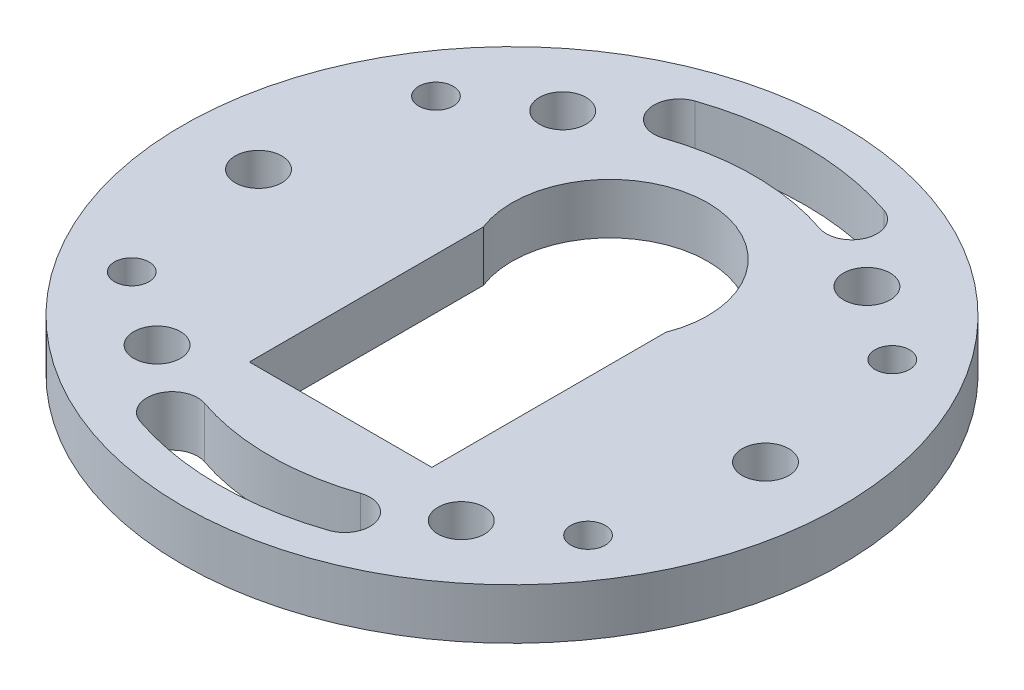
SolidWorks part; units mm, degrees
ref_plane "Front Plane" through (0, 0, 0) normal (0, 0, 1) x (1, 0, 0)
ref_plane "Top Plane" through (0, 0, 0) normal (0, 1, 0) x (1, 0, 0)
ref_plane "Right Plane" through (0, 0, 0) normal (1, 0, 0) x (0, 0, -1)
sketch "Sketch1" plane through (0, 0, 0) normal (0, 1, 0) x (1, 0, 0)
  line L0 (-15, -20) -> (-15, 20) construction
  line L1 (0, 0) -> (-25, 0) construction
  line L2 (-22.5, 15) -> (-22.5, -15) construction
  line L3 (0, 0) -> (0, 22.3159) construction
  line L4 (-8.5, 25) -> (8.5, 25) construction
  line L5 (0, 0) -> (15.5017, 0) construction
  line L6 (-8.5, -25) -> (8.5, -25) construction
  line L7 (0, -16.9) -> (0, 19.3) construction
  line L9 (-9, 6.1683) -> (-9, -16.9)
  line L10 (-9, -16.9) -> (9, -16.9)
  line L11 (9, 6.1683) -> (9, -16.9)
  line L12 (-6.4793, 8.3755) -> (9, -16.9) construction
  line L13 (-9, -16.9) -> (6.95, 9.1441) construction
  circle A0 centre (-15, 20) radius 2.3
  circle A1 centre (-22.5, 15) radius 1.7
  circle A2 centre (-15, -20) radius 2.3
  circle A3 centre (-25, 0) radius 2.3
  circle A4 centre (-22.5, -15) radius 1.7
  circle A5 centre (15, -20) radius 2.3
  circle A6 centre (22.5, -15) radius 1.7
  circle A7 centre (25, 0) radius 2.3
  circle A8 centre (22.5, 15) radius 1.7
  circle A9 centre (15, 20) radius 2.3
  circle A11 centre (0, 0) radius 32.5
  arc A12 (7.6952, 22.6331) -> (9.3048, 27.3669) centre (8.5, 25) ccw
  arc A13 (-9.3048, 27.3669) -> (-7.6952, 22.6331) centre (-8.5, 25) ccw
  arc A14 (-9.3048, 27.3669) -> (9.3048, 27.3669) centre (0, 0) cw
  arc A15 (-7.6952, 22.6331) -> (7.6952, 22.6331) centre (0, 0) cw
  arc A16 (7.6952, -22.6331) -> (9.3048, -27.3669) centre (8.5, -25) cw
  arc A17 (-9.3048, -27.3669) -> (-7.6952, -22.6331) centre (-8.5, -25) cw
  arc A18 (-9.3048, -27.3669) -> (9.3048, -27.3669) centre (0, 0) ccw
  arc A19 (-7.6952, -22.6331) -> (7.6952, -22.6331) centre (0, 0) ccw
  arc A20 (9, 6.1683) -> (-9, 6.1683) centre (0, 9.65) ccw
  point P38 (0, 0)
  point P39 (0, -2.2043)
  point P46 (-6.4793, 8.3755)
  dimension "D1" = 4.6
  dimension "D2" = 3.4
  dimension "D3" = 4.6
  dimension "D4" = 4.6
  dimension "D9" = 3.4
  dimension "D13" = 65
  dimension "D14" = 19.3
  dimension "D15" = 5
  dimension "D16" = 5
  dimension "D5" = 15
  dimension "D6" = 20
  dimension "D7" = 20
  dimension "D8" = 25
  dimension "D10" = 15
  dimension "D11" = 15
  dimension "D12" = 22.5
  dimension "D17" = 8.5
  dimension "D18" = 8.5
  dimension "D19" = 25
  dimension "D20" = 18
  dimension "D21" = 36.2
  dimension "D22" = 0.7
extrude "Boss-Extrude1" add sketch "Sketch1" along normal blind 5
